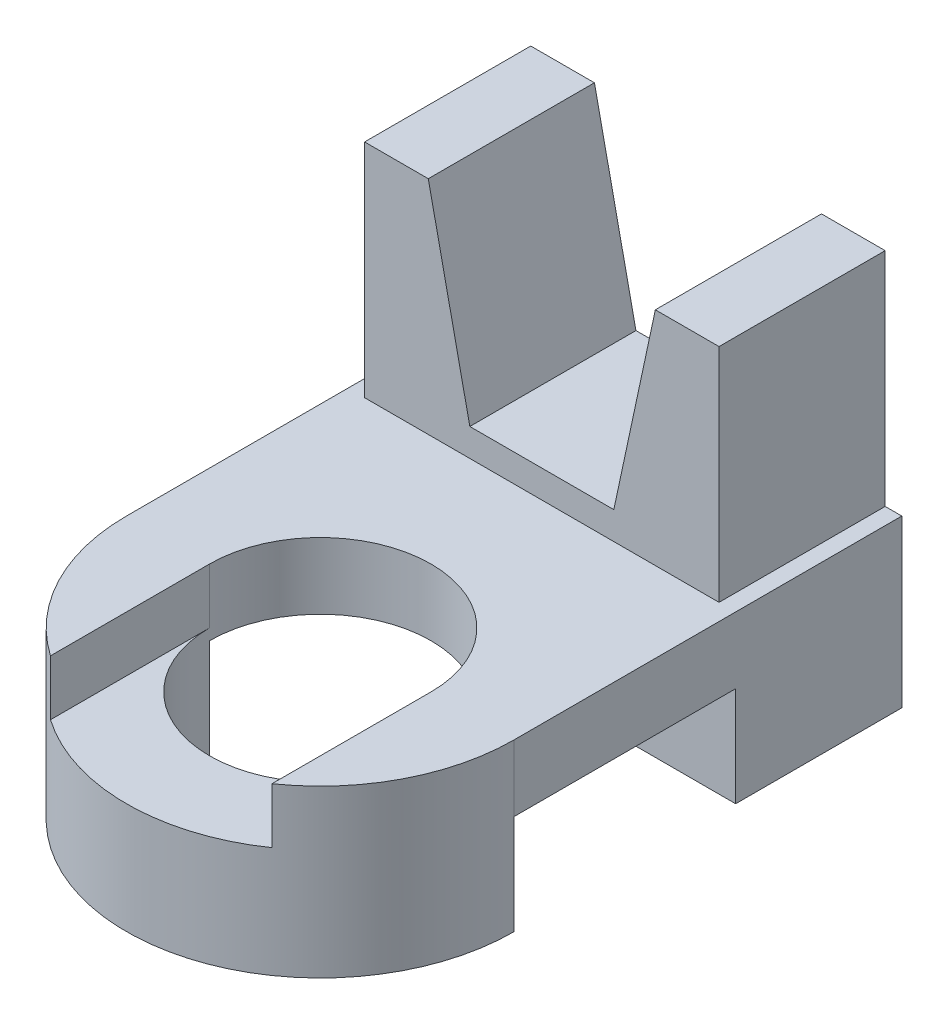
SolidWorks part; units mm, degrees
ref_plane "Front Plane" through (0, 0, 0) normal (0, 0, 1) x (1, 0, 0)
ref_plane "Top Plane" through (0, 0, 0) normal (0, 1, 0) x (1, 0, 0)
ref_plane "Right Plane" through (0, 0, 0) normal (1, 0, 0) x (0, 0, -1)
sketch "Sketch1" plane through (0, 0, 0) normal (0, 1, 0) x (1, 0, 0)
  line L1 (-35, -35) -> (-35, 35)
  line L2 (35, -35) -> (35, 35)
  line L3 (-35, 35) -> (35, 35)
  line L4 (-35, -35) -> (35, 35) construction
  line L5 (35, -35) -> (-35, 35) construction
  line L6 (-35, 5) -> (35, 5)
  arc A0 (-35, -35) -> (35, -35) centre (0, -35) ccw
  circle A1 centre (0, -35) radius 20
  point P1 (0, 0)
  dimension "D3" = 40
  dimension "D1" = 70
  dimension "D2" = 70
  dimension "D4" = 30
  dimension "D5" = 70
extrude "Boss-Extrude1" add sketch "Sketch1" along normal blind 30 contours L1 A0 L2 L6 A1 | L1 L6 L2 L3
sketch "Sketch2" plane through (35, 0, 0) normal (1, 0, 0) x (0, 0, -1)
  line L0 (-35, 0) -> (35, 0) construction
  line L1 (-35, 0) -> (5, 0)
  line L2 (-35, 0) -> (-35, 18)
  line L3 (-35, 18) -> (5, 18)
  line L4 (5, 0) -> (5, 18)
  dimension "D1" = 40
  dimension "D2" = 18
  dimension "D3" = 30
extrude "Cut-Extrude1" cut sketch "Sketch2" against normal blind 70
sketch "Sketch3" plane through (0, 30, 0) normal (0, 1, 0) x (1, 0, 0)
  line L0 (20, -35) -> (20, -91.6911)
  line L1 (-20, -35) -> (-20, -91.6911)
  line L2 (-20, -91.6911) -> (20, -91.6911)
  arc A0 (20, -35) -> (-20, -35) centre (0, -35) ccw
extrude "Cut-Extrude2" cut sketch "Sketch3" against normal blind 10
sketch "Sketch4" plane through (0, 30, 0) normal (0, 1, 0) x (1, 0, 0)
  line L0 (-35, 35) -> (35, 35) construction
  line L1 (-32, 35) -> (32, 35)
  line L2 (-32, 35) -> (-32, 5)
  line L3 (-32, 5) -> (32, 5)
  line L4 (32, 35) -> (32, 5)
  point P6 (0, 35)
  point P7 (0, 35)
  dimension "D1" = 64
  dimension "D2" = 30
extrude "Boss-Extrude2" add sketch "Sketch4" along normal blind 40
sketch "Sketch5" plane through (0, 0, -5) normal (0, 0, 1) x (1, 0, 0)
  line L0 (0, 70) -> (0, 35) construction
  line L1 (-32, 70) -> (32, 70) construction
  line L2 (-20.5, 70) -> (20.5, 70)
  line L3 (-13, 35) -> (13, 35)
  line L4 (13, 35) -> (20.5, 70)
  line L5 (-13, 35) -> (-20.5, 70)
  point P8 (0, 70)
  point P11 (0, 35)
  dimension "D1" = 35
  dimension "D2" = 26
  dimension "D3" = 41
extrude "Cut-Extrude3" cut sketch "Sketch5" against normal through all
